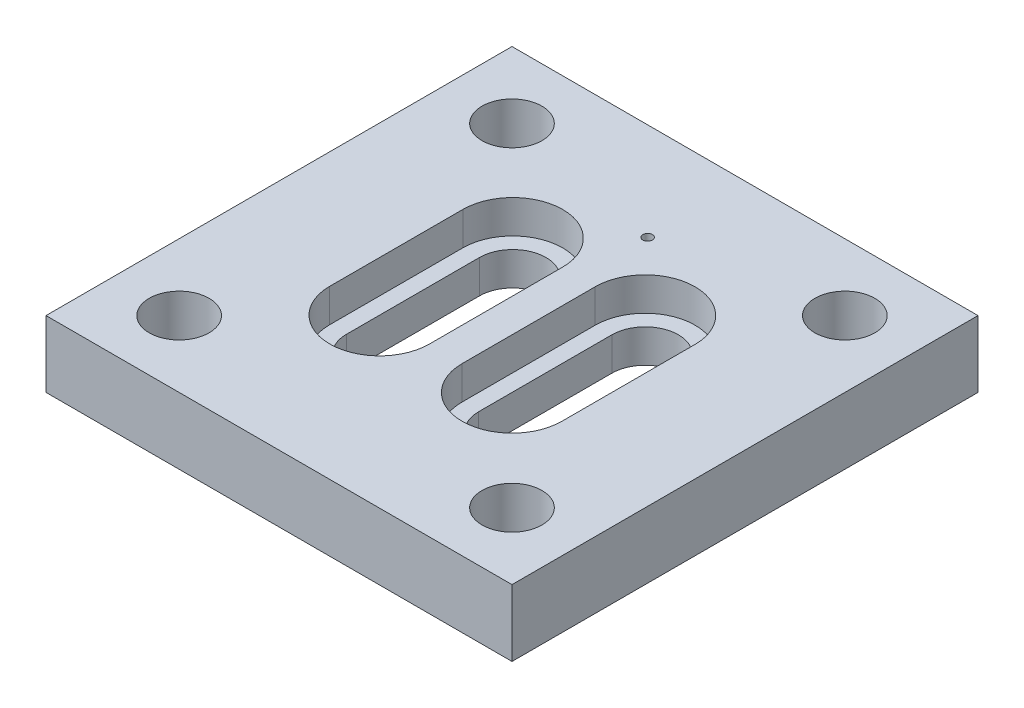
SolidWorks part; units mm, degrees
ref_plane "Ön Düzlem" through (0, 0, 0) normal (0, 0, 1) x (1, 0, 0)
ref_plane "Üst Düzlem" through (0, 0, 0) normal (0, 1, 0) x (1, 0, 0)
ref_plane "Sağ Düzlem" through (0, 0, 0) normal (1, 0, 0) x (0, 0, -1)
sketch "Çizim1" plane through (0, 0, 0) normal (0, 1, 0) x (1, 0, 0)
  line L1 (-70, 70) -> (70, 70)
  line L2 (-70, 70) -> (-70, -70)
  line L3 (-70, -70) -> (70, -70)
  line L4 (70, 70) -> (70, -70)
  line L5 (-70, 70) -> (70, -70) construction
  line L6 (-70, -70) -> (70, 70) construction
  circle A0 centre (-50, 50) radius 9
  circle A1 centre (50, 50) radius 9
  circle A2 centre (-50, -50) radius 9
  circle A3 centre (50, -50) radius 9
  point P0 (0, 0)
  point P14 (0, 0)
  point P15 (0, 0)
  point P16 (0, 0)
  point P17 (0, 0)
  dimension "D3" = 18
  dimension "D4" = 20
  dimension "D6" = 20
  dimension "D7" = 20
  dimension "D1" = 140
  dimension "D2" = 140
  dimension "D5" = 20
extrude "Yükseklik-Ekstrüzyon1" add sketch "Çizim1" against normal blind 20
sketch "Çizim2" plane through (0, -20, 0) normal (0, -1, 0) x (-1, 0, 0)
  line L0 (-20, 20) -> (-20, -20) construction
  line L1 (-10, 20) -> (-10, -20)
  line L2 (-30, 20) -> (-30, -20)
  line L3 (20, 20.2272) -> (20, -19.7728) construction
  line L4 (30, 20.2272) -> (30, -19.7728)
  line L5 (10, 20.2272) -> (10, -19.7728)
  arc A0 (-10, 20) -> (-30, 20) centre (-20, 20) ccw
  arc A1 (-30, -20) -> (-10, -20) centre (-20, -20) ccw
  arc A2 (30, 20.2272) -> (10, 20.2272) centre (20, 20.2272) ccw
  arc A3 (10, -19.7728) -> (30, -19.7728) centre (20, -19.7728) ccw
  point P2 (-20, 0)
  point P7 (20, 0.2272)
  dimension "D1" = 10
  dimension "D5" = 20
  dimension "D2" = 40
  dimension "D3" = 40
  dimension "D4" = 10
sketch "Çizim4" plane through (0, 0, 0) normal (0, 1, 0) x (1, 0, 0)
  line L0 (-30, 20.2272) -> (-30, -19.7728) construction
  line L1 (-10, 20.2272) -> (-10, -19.7728) construction
  line L2 (30, 20) -> (30, -20) construction
  line L3 (10, 20) -> (10, -20) construction
  line L4 (-30, 20.2272) -> (-30, -19.7728)
  line L5 (-10, 20.2272) -> (-10, -19.7728)
  line L6 (30, 20) -> (30, -20)
  line L7 (10, 20) -> (10, -20)
  line L8 (-5, 20.2272) -> (-5, -19.7728)
  line L9 (-35, 20.2272) -> (-35, -19.7728)
  line L10 (35, 20) -> (35, -20)
  line L11 (5, 20) -> (5, -20)
  arc A0 (-30, -19.7728) -> (-10, -19.7728) centre (-20, -19.7728) ccw construction
  arc A1 (-10, 20.2272) -> (-30, 20.2272) centre (-20, 20.2272) ccw construction
  arc A2 (10, -20) -> (30, -20) centre (20, -20) ccw construction
  arc A3 (30, 20) -> (10, 20) centre (20, 20) ccw construction
  arc A4 (-30, -19.7728) -> (-10, -19.7728) centre (-20, -19.7728) ccw
  arc A5 (-10, 20.2272) -> (-30, 20.2272) centre (-20, 20.2272) ccw
  arc A6 (10, -20) -> (30, -20) centre (20, -20) ccw
  arc A7 (30, 20) -> (10, 20) centre (20, 20) ccw
  arc A8 (-35, -19.7728) -> (-5, -19.7728) centre (-20, -19.7728) ccw
  arc A9 (-5, 20.2272) -> (-35, 20.2272) centre (-20, 20.2272) ccw
  arc A10 (5, -20) -> (35, -20) centre (20, -20) ccw
  arc A11 (35, 20) -> (5, 20) centre (20, 20) ccw
  dimension "D1" = 5
  dimension "D2" = 5
extrude "Kes-Ekstrüzyon1" cut sketch "Çizim4" against normal blind 10
extrude "Kes-Ekstrüzyon2" cut sketch "Çizim2" against normal through all
hole_wizard "#6-40 Dişli Delik1" positions "Çizim7" profile "Çizim6" tap size "#6-40" standard "ANSI İnç" end condition through all
sketch "Çizim7" plane through (0, 0, 0) normal (0, 1, 0) x (1, 0, 0)
  point P0 (0, 40.7308)
sketch "Çizim6" plane through (0, 0, -40.7308) normal (1, 0, 0) x (0, 0, 1)
  line L0 (0, 0) -> (0, 20)
  line L1 (0, 20) -> (2.3876, 20)
  line L2 (1.4351, 19.0475) -> (1.4351, 0)
  line L5 (1.4351, 0) -> (0, 0)
  line L7 (2.3876, 20) -> (1.4351, 19.0475)
  line L8 (-2.3876, 20) -> (-1.4351, 19.0475) construction
  line L11 (0, -6.35) -> (0, 107.95) construction
  dimension "Thru Tap Drill Dia." = 2.8702
  dimension "Thru Tap Drill Depth" = 20
  dimension "Far C'Sink Dia." = 4.7752
  dimension "Far C'Sink Angle" = 90
cosmetic thread "Delik Dişi1" parameters "D2"=3.5052
